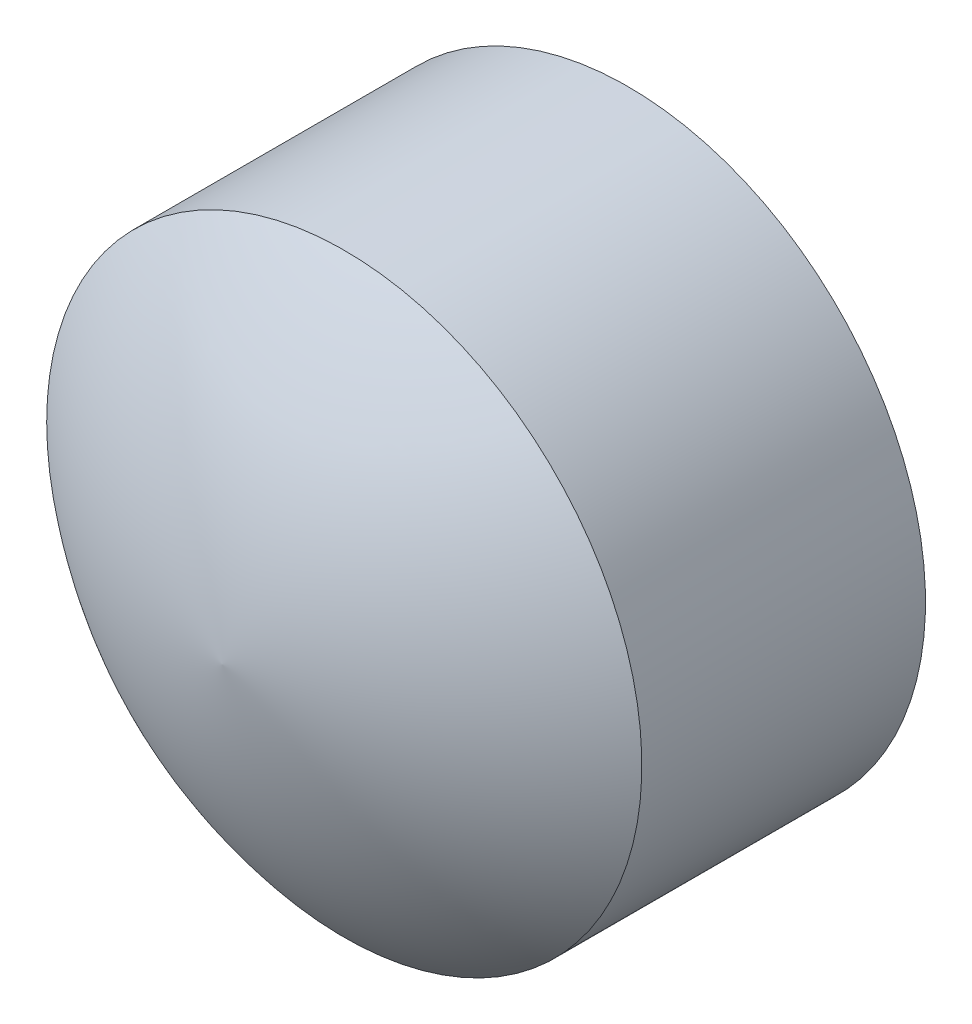
SolidWorks part; units mm, degrees
ref_plane "Front Plane" through (0, 0, 0) normal (0, 0, 1) x (1, 0, 0)
ref_plane "Top Plane" through (0, 0, 0) normal (0, 1, 0) x (1, 0, 0)
ref_plane "Right Plane" through (0, 0, 0) normal (1, 0, 0) x (0, 0, -1)
sketch "Sketch1" plane through (0, 0, 0) normal (0, 1, 0) x (1, 0, 0)
  line L0 (0, 0) -> (6, 0)
  line L1 (6, 0) -> (6, 10)
  line L2 (6, 10) -> (11, 10)
  line L3 (11, 10) -> (11, -0.4851)
  line L4 (0, 0) -> (0, -5)
  arc A0 (11, -0.4851) -> (0, -5) centre (-1.7508, 14.9232) cw
  dimension "D4" = 20
  dimension "D1" = 10
  dimension "D2" = 5
  dimension "D3" = 6
  dimension "D5" = 5
revolve "Revolve1" add sketch "Sketch1" angle 360 about L4
